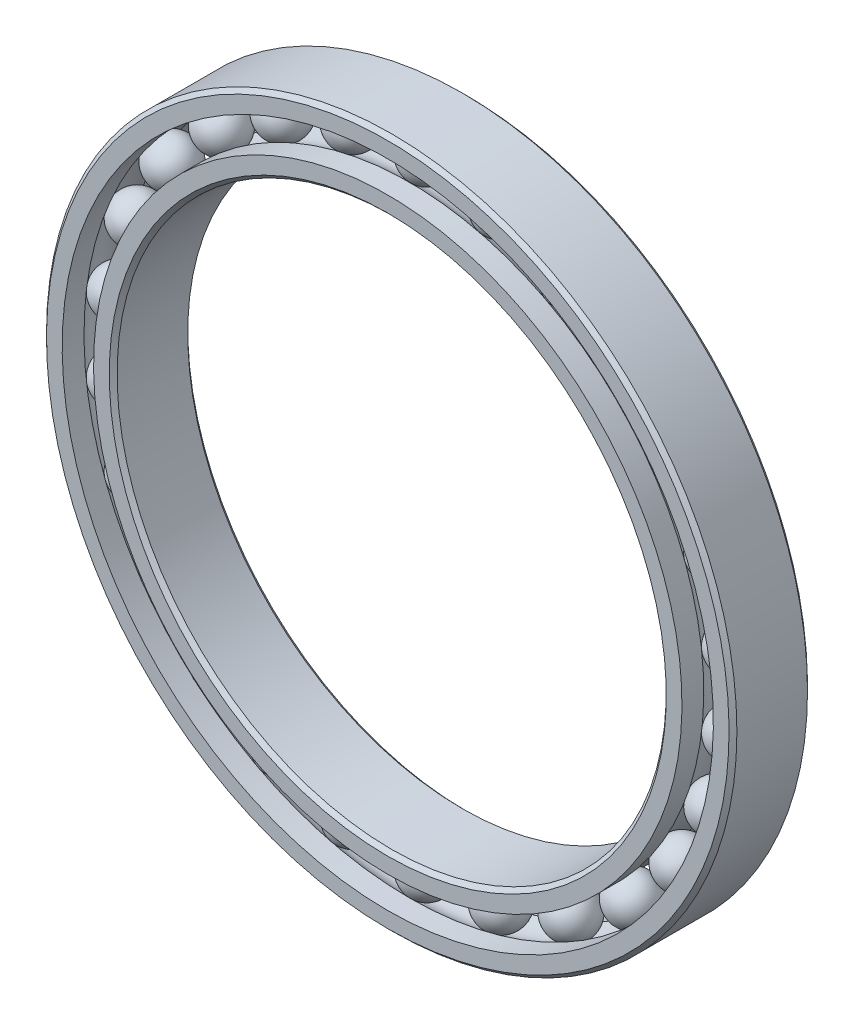
SolidWorks part; units mm, degrees
ref_plane "Front Plane" through (0, 0, 0) normal (0, 0, 1) x (1, 0, 0)
ref_plane "Top Plane" through (0, 0, 0) normal (0, 1, 0) x (1, 0, 0)
ref_plane "Right Plane" through (0, 0, 0) normal (1, 0, 0) x (0, 0, -1)
sketch "Sketch1" plane through (0, 0, 0) normal (0, 0, 1) x (1, 0, 0)
  circle A0 centre (0, 0) radius 22
  circle A1 centre (0, 0) radius 17.5
  dimension "OD" = 44
  dimension "ID" = 35
  dimension "For Shaft Diameter" = 35
  dimension "For Housing ID" = 44
sketch "Sketch5" plane through (0, 0, 0) normal (1, 0, 0) x (0, 0, -1)
  line L0 (-2.5, 0) -> (2.5, 0) construction
  line L1 (0, 22) -> (0, -22) construction
  line L2 (2.25, 22) -> (-2.25, 22)
  line L3 (-2.25, 22) -> (-2.5, 21.75)
  line L4 (-2.5, 21.75) -> (-2.5, 20.75)
  line L5 (-2.5, 20.75) -> (-1.1111, 20.75)
  line L6 (2.5, 20.75) -> (1.1111, 20.75)
  line L7 (2.5, 21.75) -> (2.5, 20.75)
  line L8 (2.25, 22) -> (2.5, 21.75)
  line L9 (0, 22) -> (0, 19.75) construction
  line L10 (0, 19.75) -> (0, 17.5) construction
  line L11 (-1.4948, 19.75) -> (-2.5, 19.75) construction
  line L12 (1.8069, 18.7754) -> (2.1879, 18.7754) construction
  line L13 (-1.8069, 18.7754) -> (-2.1879, 18.7754) construction
  line L14 (-1.8069, 18.7754) -> (-1.8069, 20.7246) construction
  line L15 (-1.8069, 20.7246) -> (-2.1879, 20.7246) construction
  line L16 (-2.1879, 18.7754) -> (-2.1879, 20.7246) construction
  line L17 (-1.8069, 18.7754) -> (-2.1879, 20.7246) construction
  line L18 (-1.8069, 20.7246) -> (-2.1879, 18.7754) construction
  line L19 (2.1879, 18.7754) -> (2.1879, 20.7246) construction
  line L20 (1.8069, 20.7246) -> (2.1879, 20.7246) construction
  line L21 (1.8069, 18.7754) -> (1.8069, 20.7246) construction
  line L22 (0, 22) -> (0, -22) construction
  arc A0 (-1.1111, 20.75) -> (1.1111, 20.75) centre (0, 19.75) cw
  circle A1 centre (0, 19.75) radius 1.4948 construction
  point P14 (0, 17.5)
  point P15 (-1.9974, 19.75)
  dimension "D1" = 45
  dimension "D2" = 0.25
  dimension "D3" = 2.2222
  dimension "D4" = 1
  dimension "D5" = 0.381
  dimension "D6" = 0.0254
  dimension "Width" = 5
sketch "Sketch6" plane through (0, 0, 0) normal (1, 0, 0) x (0, 0, -1)
  line L0 (2.25, 22) -> (2.5, 21.75) construction
  line L1 (2.5, 21.75) -> (2.5, 20.75) construction
  line L2 (2.5, 20.75) -> (1.1111, 20.75) construction
  line L3 (-2.5, 20.75) -> (-1.1111, 20.75) construction
  line L4 (-2.5, 21.75) -> (-2.5, 20.75) construction
  line L5 (-2.25, 22) -> (-2.5, 21.75) construction
  line L6 (2.25, 22) -> (-2.25, 22) construction
  line L7 (2.25, 22) -> (2.5, 21.75)
  line L8 (2.5, 21.75) -> (2.5, 20.75)
  line L9 (2.5, 20.75) -> (1.1111, 20.75)
  line L10 (-2.5, 20.75) -> (-1.1111, 20.75)
  line L11 (-2.5, 21.75) -> (-2.5, 20.75)
  line L12 (-2.25, 22) -> (-2.5, 21.75)
  line L13 (2.25, 22) -> (-2.25, 22)
  arc A0 (1.1111, 20.75) -> (-1.1111, 20.75) centre (0, 19.75) ccw construction
  arc A1 (1.1111, 20.75) -> (-1.1111, 20.75) centre (0, 19.75) ccw
revolve "Revolve5" add sketch "Sketch6" angle 360 about L0
sketch "Sketch3" plane through (0, 0, 0) normal (1, 0, 0) x (0, 0, -1)
  line L0 (-2.5, 18.75) -> (-1.1111, 18.75)
  line L1 (0, 22) -> (0, -22) construction
  line L2 (-2.5, 21.75) -> (-2.5, 20.75) construction
  line L3 (-2.5, 18.75) -> (-2.5, 17.75)
  line L4 (-2.25, 22) -> (-2.5, 21.75) construction
  line L5 (-2.5, 17.75) -> (-2.25, 17.5)
  line L6 (-2.25, 17.5) -> (2.25, 17.5)
  line L8 (2.25, 17.5) -> (2.5, 17.75)
  line L10 (2.5, 17.75) -> (2.5, 18.75)
  line L11 (2.5, 18.75) -> (1.1111, 18.75)
  line L12 (2.25, 22) -> (2.25, -22) construction
  line L13 (2.25, 22) -> (2.5, 21.75) construction
  line L14 (2.5, -21.75) -> (2.5, 21.75) construction
  arc A0 (1.1111, 20.75) -> (-1.1111, 20.75) centre (0, 19.75) ccw construction
  arc A1 (1.1111, 18.75) -> (-1.1111, 18.75) centre (0, 19.75) cw
revolve "Revolve3" add sketch "Sketch3" angle 360 about L0
sketch "Sketch4" plane through (0, 0, 0) normal (1, 0, 0) x (0, 0, -1)
  line L0 (-1.4948, 19.75) -> (1.4948, 19.75)
  arc A2 (-1.4948, 19.75) -> (1.4948, 19.75) centre (0, 19.75) cw
  arc A3 (1.1111, 20.75) -> (-1.1111, 20.75) centre (0, 19.75) ccw construction
revolve "Revolve4" add sketch "Sketch4" angle 360 about L0
pattern_circular "CirPattern1" count 26 over 360 about axis through (0, 0, 0) along (0, 0, 1) of bodies 104
equation "\"D2@Sketch5\" = \"Width@Sketch5\" * .05"
equation "\"D3@Sketch5\" = \"Width@Sketch5\" / 2.25"
equation "\"D4@Sketch5\"=((\"OD@Sketch1\"-\"ID@Sketch1\")/2)/4.5"
